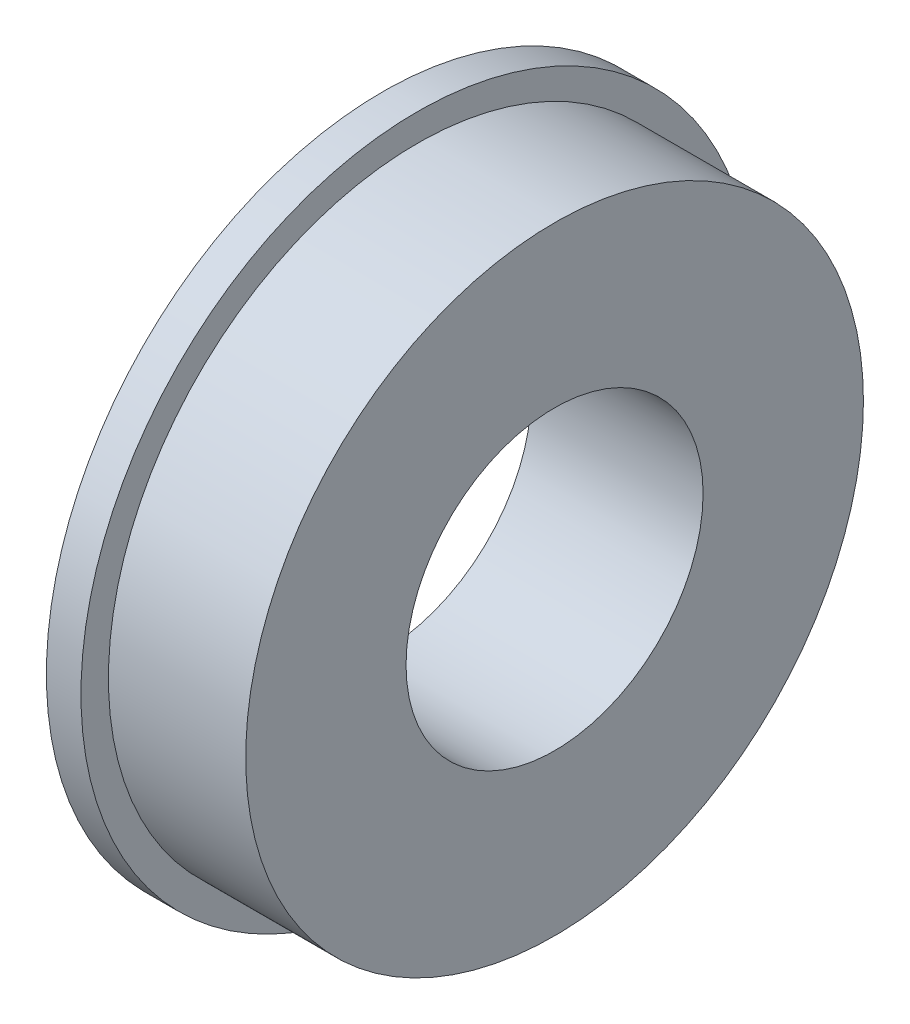
SolidWorks part; units mm, degrees
ref_plane "Front Plane" through (0, 0, 0) normal (0, 0, 1) x (1, 0, 0)
ref_plane "Top Plane" through (0, 0, 0) normal (0, 1, 0) x (1, 0, 0)
ref_plane "Right Plane" through (0, 0, 0) normal (1, 0, 0) x (0, 0, -1)
sketch "Sketch5" plane through (0, 0, 0) normal (0, 0, 1) x (1, 0, 0)
  line L0 (0, 0) -> (0, 7.9502)
  line L1 (0, 0) -> (14.2875, 0)
  line L2 (14.2875, 0) -> (14.2875, 6.35)
  line L3 (14.2875, 6.35) -> (15.5575, 6.35)
  line L4 (15.5575, 6.35) -> (15.5575, 7.9502)
  line L5 (15.5575, 7.9502) -> (12.6619, 7.9502)
  line L6 (12.6619, 7.9502) -> (12.6619, 7.3152)
  line L7 (12.6619, 7.3152) -> (9.7663, 7.3152)
  line L8 (9.7663, 7.3152) -> (9.7663, 7.9502)
  line L9 (9.7663, 7.9502) -> (0, 7.9502)
  line L10 (6.8707, 7.9502) -> (6.8707, 0)
  point P3 (0, 0)
  dimension "D1" = 14.2875
  dimension "D2" = 7.9502
  dimension "D3" = 1.27
  dimension "D4" = 6.35
  dimension "D5" = 0.635
  dimension "D6" = 2.8956
  dimension "D7" = 2.8956
  dimension "D8" = 6.8707
revolve "Revolve1" add sketch "Sketch5" angle 360 about L0
move or copy body "Body-Move/Copy1" bodies to move or copy 106 copy no rotation origin (0, 3.9751, 0) rotation axis (0, 0, 1) rotation angle 90
